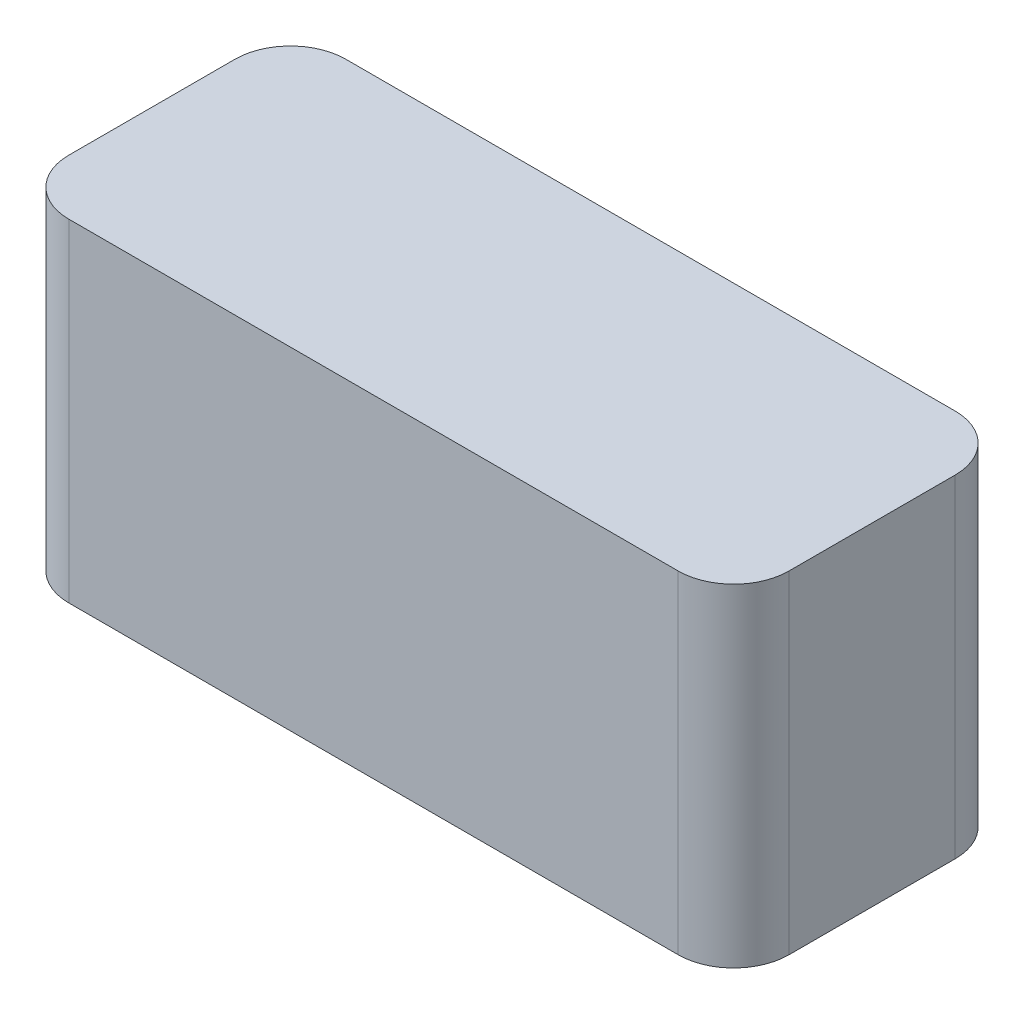
SolidWorks part; units mm, degrees
ref_plane "Front Plane" through (0, 0, 0) normal (0, 0, 1) x (1, 0, 0)
ref_plane "Top Plane" through (0, 0, 0) normal (0, 1, 0) x (1, 0, 0)
ref_plane "Right Plane" through (0, 0, 0) normal (1, 0, 0) x (0, 0, -1)
sketch "Sketch1" plane through (0, 0, 0) normal (0, 1, 0) x (1, 0, 0)
  line L1 (-32.5, -12.5) -> (32.5, -12.5)
  line L2 (-32.5, -12.5) -> (-32.5, 12.5)
  line L3 (-32.5, 12.5) -> (32.5, 12.5)
  line L4 (32.5, -12.5) -> (32.5, 12.5)
  line L5 (-32.5, -12.5) -> (32.5, 12.5) construction
  line L6 (-32.5, 12.5) -> (32.5, -12.5) construction
  point P0 (0, 0)
  dimension "D1" = 65
  dimension "D2" = 25
extrude "Boss-Extrude1" add sketch "Sketch1" along normal blind 30
fillet "Fillet1" radius 5 4 edges at (-32.5, 15, -12.5) (32.5, 15, -12.5) (32.5, 15, 12.5) (-32.5, 15, 12.5)
